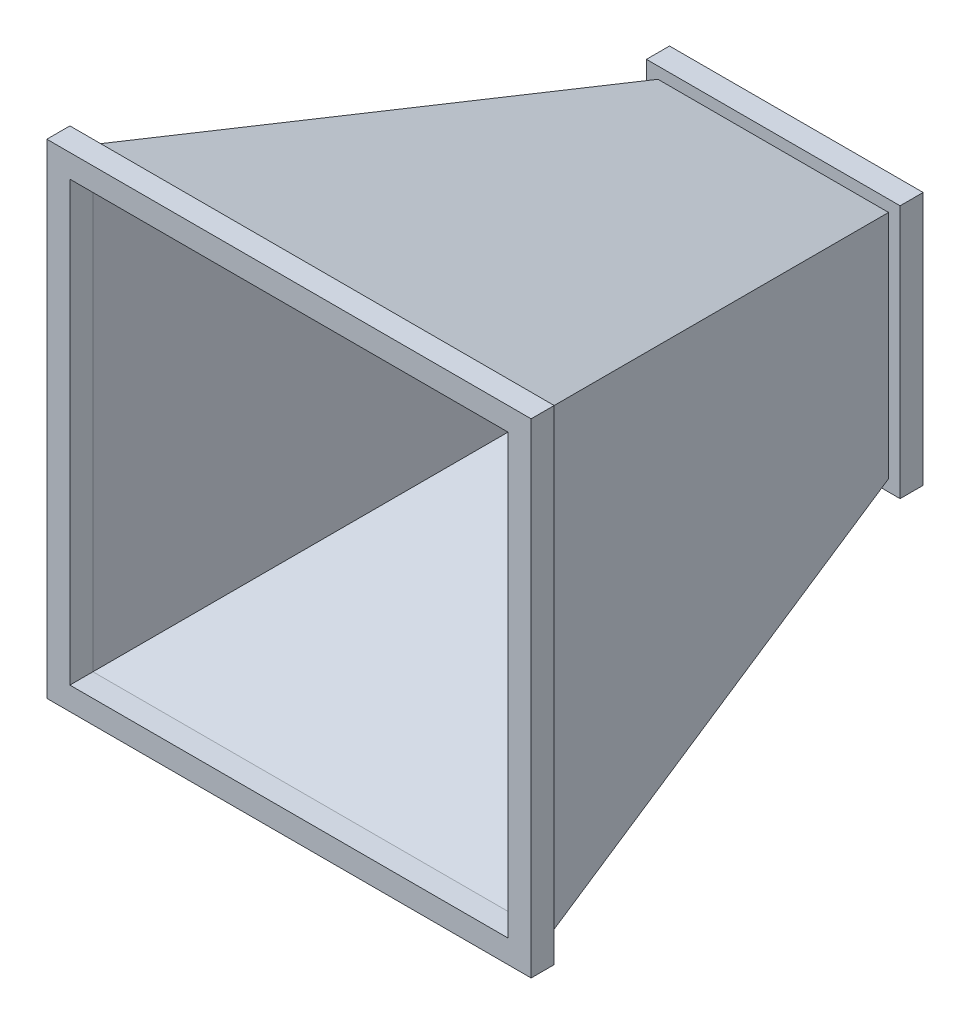
SolidWorks part; units mm, degrees
ref_plane "Front Plane" through (0, 0, 0) normal (0, 0, 1) x (1, 0, 0)
ref_plane "Top Plane" through (0, 0, 0) normal (0, 1, 0) x (1, 0, 0)
ref_plane "Right Plane" through (0, 0, 0) normal (1, 0, 0) x (0, 0, -1)
sketch "Sketch1" plane through (0, 0, 0) normal (0, 0, 1) x (1, 0, 0)
  line L1 (-127, -127) -> (127, -127)
  line L2 (-127, -127) -> (-127, 127)
  line L3 (-127, 127) -> (127, 127)
  line L4 (127, -127) -> (127, 127)
  line L5 (-127, -127) -> (127, 127) construction
  line L6 (-127, 127) -> (127, -127) construction
  point P0 (0, 0)
  dimension "D1" = 254
  dimension "D2" = 254
ref_plane "Plane1" through (0, 0, 508) normal (0, 0, 1) x (1, 0, 0)
sketch "Sketch2" plane through (0, 0, 508) normal (0, 0, 1) x (1, 0, 0)
  line L1 (-254, -254) -> (254, -254)
  line L2 (-254, -254) -> (-254, 254)
  line L3 (-254, 254) -> (254, 254)
  line L4 (254, -254) -> (254, 254)
  line L5 (-254, -254) -> (254, 254) construction
  line L6 (-254, 254) -> (254, -254) construction
  point P0 (0, 0)
  dimension "D1" = 508
  dimension "D2" = 508
loft "Loft1" add profiles "Sketch2", "Sketch1"
sketch "Sketch3" plane through (0, 0, 508) normal (0, 0, 1) x (1, 0, 0)
  line L14 (241.3, -241.3) -> (241.3, 241.3)
  line L15 (-241.3, -241.3) -> (241.3, -241.3)
  line L16 (-241.3, 241.3) -> (-241.3, -241.3)
  line L17 (241.3, 241.3) -> (-241.3, 241.3)
  line L18 (241.3, -241.3) -> (241.3, 241.3)
  line L19 (-241.3, -241.3) -> (241.3, -241.3)
  line L20 (-241.3, 241.3) -> (-241.3, -241.3)
  line L21 (241.3, 241.3) -> (-241.3, 241.3)
  dimension "D1" = 12.7
sketch "Sketch4" plane through (0, 0, 0) normal (0, 0, -1) x (-1, 0, 0)
  line L14 (114.3, -114.3) -> (114.3, 114.3)
  line L15 (-114.3, -114.3) -> (114.3, -114.3)
  line L16 (-114.3, 114.3) -> (-114.3, -114.3)
  line L17 (114.3, 114.3) -> (-114.3, 114.3)
  line L18 (114.3, -114.3) -> (114.3, 114.3)
  line L19 (-114.3, -114.3) -> (114.3, -114.3)
  line L20 (-114.3, 114.3) -> (-114.3, -114.3)
  line L21 (114.3, 114.3) -> (-114.3, 114.3)
  dimension "D1" = 12.7
loft "Cut-Loft1" cut profiles "Sketch4", "Sketch3"
sketch "Sketch5" plane through (0, 0, 508) normal (0, 0, 1) x (1, 0, 0)
  line L1 (-241.3, -241.3) -> (241.3, -241.3)
  line L2 (-241.3, -241.3) -> (-241.3, 241.3)
  line L3 (-241.3, 241.3) -> (241.3, 241.3)
  line L4 (241.3, -241.3) -> (241.3, 241.3)
  line L5 (-241.3, -241.3) -> (241.3, 241.3) construction
  line L6 (-241.3, 241.3) -> (241.3, -241.3) construction
  line L15 (266.7, -266.7) -> (266.7, 266.7)
  line L16 (-266.7, -266.7) -> (266.7, -266.7)
  line L17 (-266.7, 266.7) -> (-266.7, -266.7)
  line L18 (266.7, 266.7) -> (-266.7, 266.7)
  line L19 (266.7, -266.7) -> (266.7, 266.7)
  line L20 (-266.7, -266.7) -> (266.7, -266.7)
  line L21 (-266.7, 266.7) -> (-266.7, -266.7)
  line L22 (266.7, 266.7) -> (-266.7, 266.7)
  point P0 (0, 0)
  dimension "D1" = 12.7
extrude "Boss-Extrude1" add sketch "Sketch5" along normal blind 25.4
sketch "Sketch6" plane through (0, 0, 0) normal (0, 0, -1) x (-1, 0, 0)
  line L1 (-114.3, -114.3) -> (114.3, -114.3)
  line L2 (-114.3, -114.3) -> (-114.3, 114.3)
  line L3 (-114.3, 114.3) -> (114.3, 114.3)
  line L4 (114.3, -114.3) -> (114.3, 114.3)
  line L5 (-114.3, -114.3) -> (114.3, 114.3) construction
  line L6 (-114.3, 114.3) -> (114.3, -114.3) construction
  line L20 (139.7, -139.7) -> (139.7, 139.7)
  line L21 (-139.7, -139.7) -> (139.7, -139.7)
  line L22 (-139.7, 139.7) -> (-139.7, -139.7)
  line L23 (139.7, 139.7) -> (-139.7, 139.7)
  line L24 (139.7, -139.7) -> (139.7, 139.7)
  line L25 (-139.7, -139.7) -> (139.7, -139.7)
  line L26 (-139.7, 139.7) -> (-139.7, -139.7)
  line L27 (139.7, 139.7) -> (-139.7, 139.7)
  point P0 (0, 0)
  dimension "D1" = 12.7
extrude "Boss-Extrude2" add sketch "Sketch6" along normal blind 25.4
